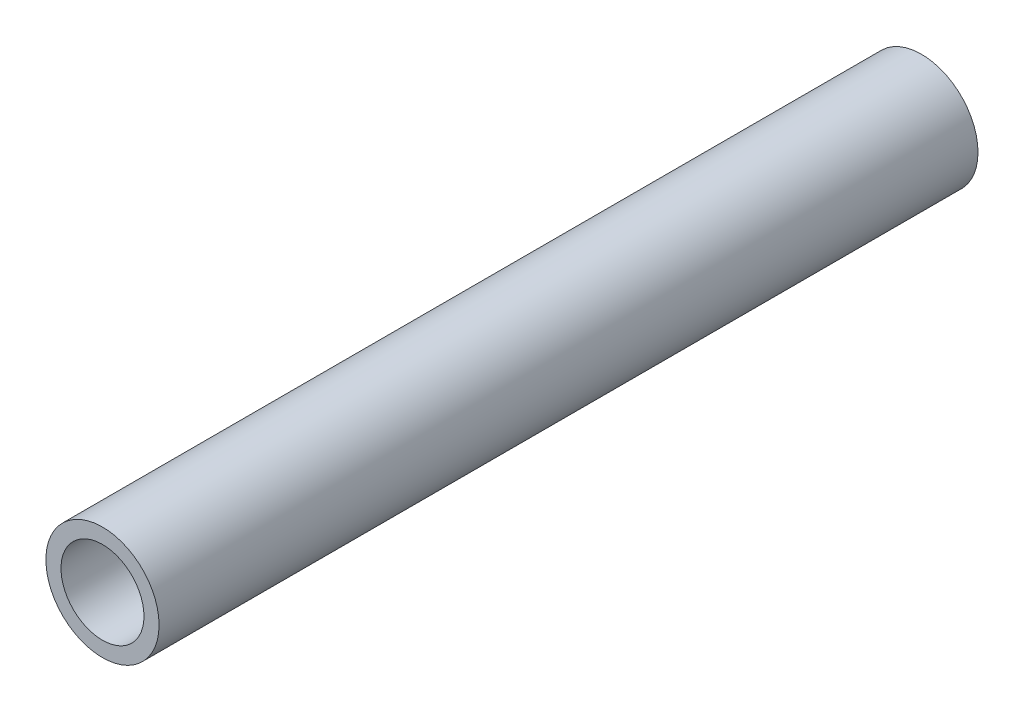
SolidWorks part; units mm, degrees
ref_plane "Front Plane" through (0, 0, 0) normal (0, 0, 1) x (1, 0, 0)
ref_plane "Top Plane" through (0, 0, 0) normal (0, 1, 0) x (1, 0, 0)
ref_plane "Right Plane" through (0, 0, 0) normal (1, 0, 0) x (0, 0, -1)
sketch "Sketch2" plane through (0, 0, 0) normal (0, 0, 1) x (1, 0, 0)
  circle A0 centre (0, 0) radius 36.8564
  circle A1 centre (0, 0) radius 27.0272
extrude "Boss-Extrude1" add sketch "Sketch2" along normal blind 533.4
